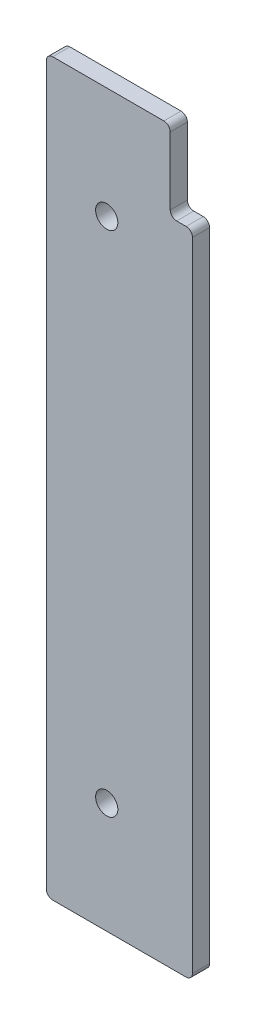
SolidWorks part; units mm, degrees
ref_plane "Front Plane" through (0, 0, 0) normal (0, 0, 1) x (1, 0, 0)
ref_plane "Top Plane" through (0, 0, 0) normal (0, 1, 0) x (1, 0, 0)
ref_plane "Right Plane" through (0, 0, 0) normal (1, 0, 0) x (0, 0, -1)
sketch "Sketch1" plane through (0, 0, 0) normal (0, 0, 1) x (1, 0, 0)
  line L0 (142.5, 205.8193) -> (141, 205.8193)
  line L1 (121.5, 218.4579) -> (139, 218.4579)
  line L2 (120.5, 217.4579) -> (120.5, 104.4579)
  line L3 (121.5, 103.4579) -> (142.5, 103.4579)
  line L4 (143.5, 204.8193) -> (143.5, 104.4579)
  line L5 (130, 205.2373) -> (130, 206.1237) construction
  line L6 (140, 206.8193) -> (140, 217.4579)
  circle A0 centre (130, 200.9413) radius 1.75
  circle A1 centre (130, 120.9413) radius 1.75
  arc A2 (120.5, 104.4579) -> (121.5, 103.4579) centre (121.5, 104.4579) ccw
  arc A3 (142.5, 103.4579) -> (143.5, 104.4579) centre (142.5, 104.4579) ccw
  arc A5 (121.5, 218.4579) -> (120.5, 217.4579) centre (121.5, 217.4579) ccw
  arc A6 (142.5, 205.8193) -> (143.5, 204.8193) centre (142.5, 204.8193) cw
  arc A7 (141, 205.8193) -> (140, 206.8193) centre (141, 206.8193) cw
  arc A8 (140, 217.4579) -> (139, 218.4579) centre (139, 217.4579) ccw
  point P17 (143.5, 103.4579)
  point P20 (143.5, 218.4579)
  point P23 (120.5, 218.4579)
  dimension "D3" = 3.5
  dimension "D4" = 3.5
  dimension "D6" = 1
  dimension "D7" = 1
  dimension "D1" = 23
  dimension "D2" = 115
  dimension "D5" = 80
extrude "Boss-Extrude1" add sketch "Sketch1" along normal blind 2.7
